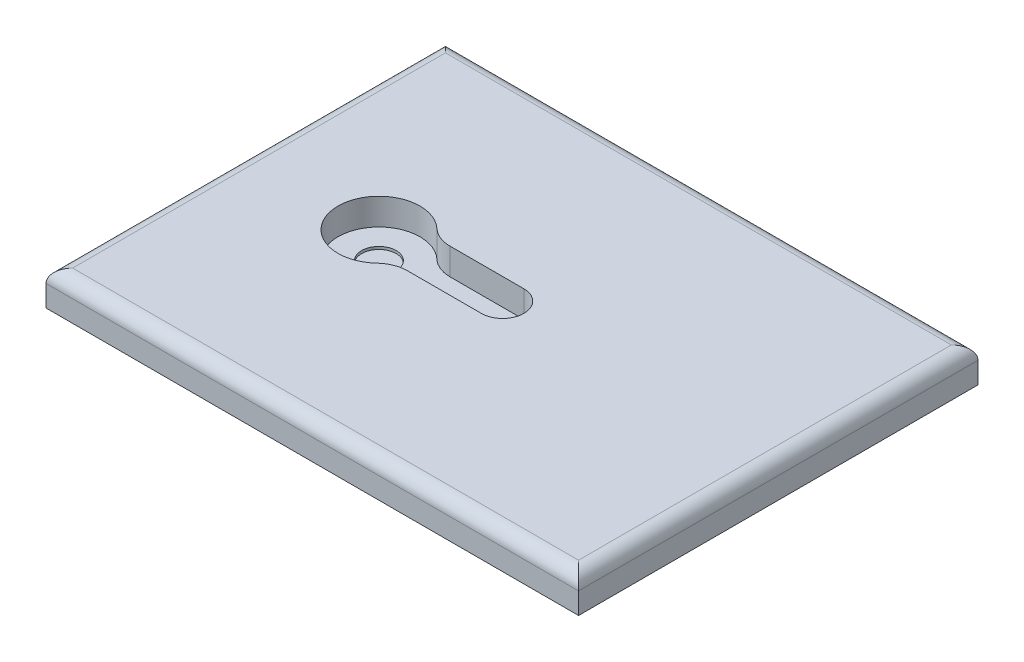
SolidWorks part; units mm, degrees
ref_plane "Front Plane" through (0, 0, 0) normal (0, 0, 1) x (1, 0, 0)
ref_plane "Top Plane" through (0, 0, 0) normal (0, 1, 0) x (1, 0, 0)
ref_plane "Right Plane" through (0, 0, 0) normal (1, 0, 0) x (0, 0, -1)
sketch "Sketch2" plane through (0, 0, 0) normal (0, 1, 0) x (1, 0, 0)
  line L0 (-35.0274, -13.5146) -> (64.9726, -13.5146) construction
  line L1 (0, 23.9854) -> (0, -51.0146) construction
  line L2 (-35.0274, 23.9854) -> (64.9726, 23.9854)
  line L3 (64.9726, 23.9854) -> (64.9726, -51.0146)
  line L4 (64.9726, -51.0146) -> (-35.0274, -51.0146)
  line L5 (-35.0274, -51.0146) -> (-35.0274, 23.9854)
  dimension "D1" = 100
  dimension "D2" = 75
extrude "Boss-Extrude1" add sketch "Sketch2" along normal blind 6.5
sketch "Sketch3" plane through (0, 6.5, 0) normal (0, 1, 0) x (1, 0, 0)
  line L0 (-35.0274, -13.5146) -> (64.9726, -13.5146) construction
  line L1 (-35.0274, 23.9854) -> (-35.0274, -51.0146) construction
  line L2 (64.9726, -51.0146) -> (64.9726, 23.9854) construction
  line L3 (-7.1941, -13.5146) -> (27.3059, -13.5146) construction
  line L4 (-3.4262, -9.5146) -> (13.2131, -9.5146)
  line L5 (-3.4262, -17.5146) -> (13.2131, -17.5146)
  arc A0 (-3.4262, -9.5146) -> (-3.4262, -17.5146) centre (-10.0057, -13.5146) ccw
  arc A1 (13.2131, -9.5146) -> (13.2131, -17.5146) centre (13.2131, -13.5146) cw
  dimension "D2" = 7.7
  dimension "D1" = 8
fillet "Fillet1" radius 2.5 4 edges at (-35.0274, 6.5, 13.5146) (14.9726, 6.5, -23.9854) (64.9726, 6.5, 13.5146) (14.9726, 6.5, 51.0146)
extrude "Cut-Extrude1" cut sketch "Sketch3" against normal blind 5
fillet "Fillet3" radius 6 2 edges at (-3.4262, 4, 17.5146) (-3.4262, 4, 9.5146)
sketch "Sketch4" plane through (0, 1.5, 0) normal (0, 1, 0) x (1, 0, 0)
  line L0 (-17.7057, -13.5146) -> (8.8479, -13.5146) construction
  line L1 (-10.0057, -5.8146) -> (-10.0057, -21.2146) construction
  circle A0 centre (-9.9921, -13.5327) radius 3.25
  arc A1 (-4.7425, -7.8942) -> (-4.7425, -19.1351) centre (-10.0057, -13.5146) ccw construction
  arc A2 (-4.7425, -7.8942) -> (-4.7425, -19.1351) centre (-10.0057, -13.5146) ccw construction
  dimension "D1" = 6.5
extrude "Cut-Extrude2" cut sketch "Sketch4" against normal blind 0.5
